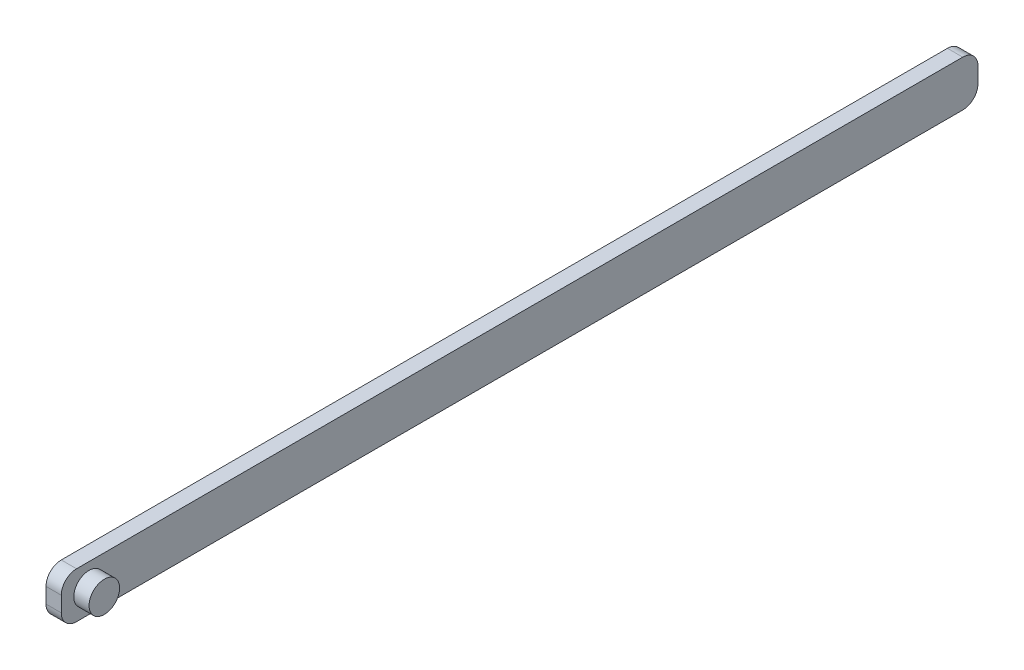
SolidWorks part; units mm, degrees
ref_plane "Front Plane" through (0, 0, 0) normal (0, 0, 1) x (1, 0, 0)
ref_plane "Top Plane" through (0, 0, 0) normal (0, 1, 0) x (1, 0, 0)
ref_plane "Right Plane" through (0, 0, 0) normal (1, 0, 0) x (0, 0, -1)
sketch "Sketch1" plane through (0, 0, 0) normal (1, 0, 0) x (0, 0, -1)
  line L1 (-19.3103, 18.9089) -> (560.6897, 18.9089)
  line L2 (-29.3103, 8.9089) -> (-29.3103, -1.0911)
  line L3 (-19.3103, -11.0911) -> (560.6897, -11.0911)
  line L4 (570.6897, 8.9089) -> (570.6897, -1.0911)
  arc A0 (560.6897, -11.0911) -> (570.6897, -1.0911) centre (560.6897, -1.0911) ccw
  arc A1 (560.6897, 18.9089) -> (570.6897, 8.9089) centre (560.6897, 8.9089) cw
  arc A2 (-29.3103, -1.0911) -> (-19.3103, -11.0911) centre (-19.3103, -1.0911) ccw
  arc A3 (-19.3103, 18.9089) -> (-29.3103, 8.9089) centre (-19.3103, 8.9089) ccw
  point P8 (570.6897, 18.9089)
  point P11 (-29.3103, -11.0911)
  point P14 (-29.3103, 18.9089)
  dimension "D3" = 10
  dimension "D1" = 30
  dimension "D2" = 600
extrude "Boss-Extrude1" add sketch "Sketch1" along normal blind 10
sketch "Sketch2" plane through (10, 0, 0) normal (1, 0, 0) x (0, 0, -1)
  circle A0 centre (-11.1353, 3.9089) radius 10
extrude "Boss-Extrude2" add sketch "Sketch2" along normal blind 10
